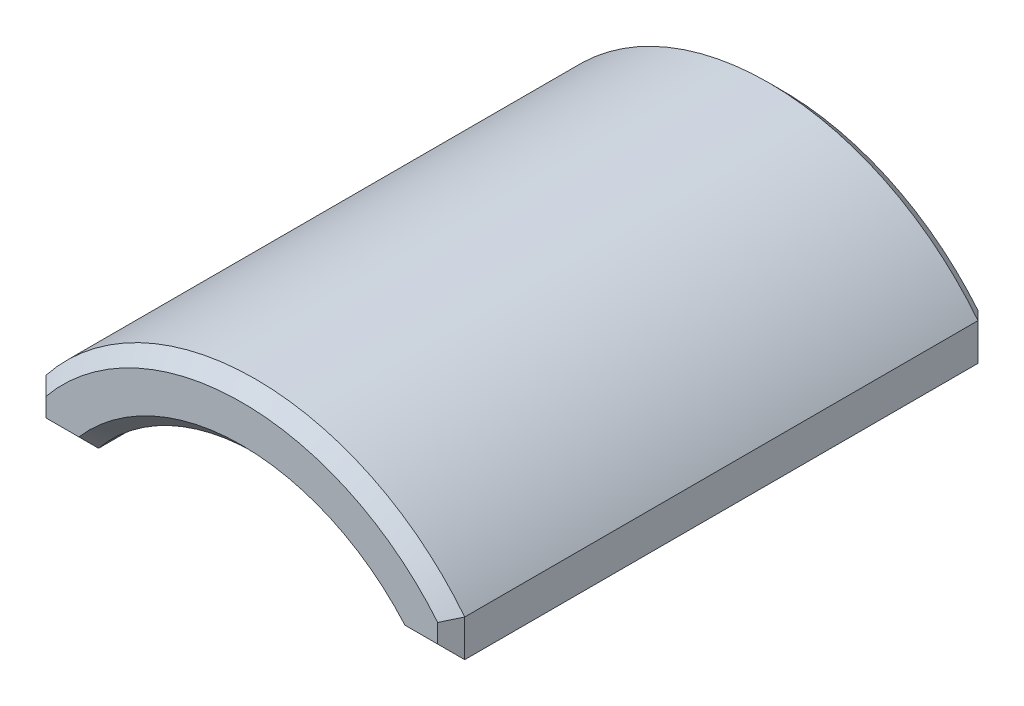
SolidWorks part; units mm, degrees
ref_plane "Face" through (0, 0, 0) normal (0, 0, 1) x (1, 0, 0)
ref_plane "Dessus" through (0, 0, 0) normal (0, 1, 0) x (1, 0, 0)
ref_plane "Droite" through (0, 0, 0) normal (1, 0, 0) x (0, 0, -1)
sketch "Esquisse1" plane through (0, 0, 0) normal (0, 0, 1) x (1, 0, 0)
  line L0 (0, 0) -> (0, 30.7501) construction
  line L1 (15.5, 12.2398) -> (15.5, 9.5)
  line L2 (-15.5, 12.2398) -> (-15.5, 9.5)
  line L3 (-15.5, 9.5) -> (-11.6082, 9.5)
  line L4 (11.6082, 9.5) -> (15.5, 9.5)
  arc A0 (15.5, 12.2398) -> (-15.5, 12.2398) centre (0, 0) ccw
  arc A1 (11.6082, 9.5) -> (-11.6082, 9.5) centre (0, 0) ccw
  dimension "D1" = 39.5
  dimension "D3" = 30
  dimension "D2" = 31
  dimension "D4" = 9.5
extrude "Base-Extrusion" add sketch "Esquisse1" along normal blind 40
chamfer "Chanfrein1" distance 1 angle 45
